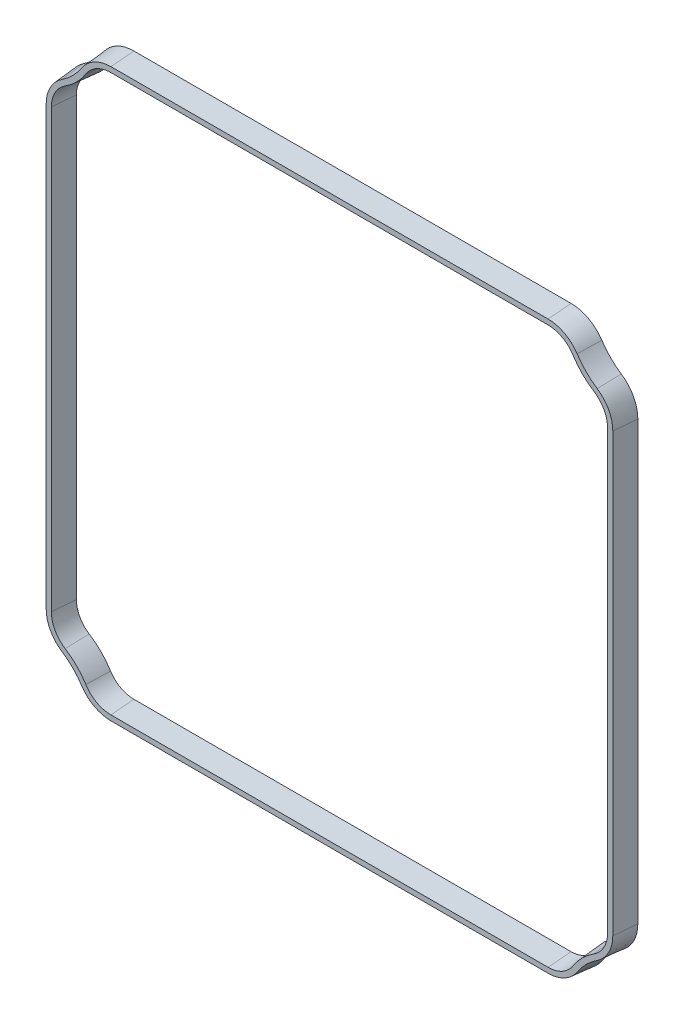
SolidWorks part; units mm, degrees
ref_plane "Front Plane" through (0, 0, 0) normal (0, 0, 1) x (1, 0, 0)
ref_plane "Top Plane" through (0, 0, 0) normal (0, 1, 0) x (1, 0, 0)
ref_plane "Right Plane" through (0, 0, 0) normal (1, 0, 0) x (0, 0, -1)
sketch "Sketch1" plane through (0, 0, 0) normal (0, 0, 1) x (1, 0, 0)
  line L4 (64.5, 11.25) -> (64.5, 58.75)
  line L5 (10.75, 5) -> (58.25, 5)
  line L6 (4.5, 58.75) -> (4.5, 11.25)
  line L7 (58.25, 65) -> (10.75, 65)
  line L8 (64.5, 11.25) -> (64.5, 58.75)
  line L9 (10.75, 5) -> (58.25, 5)
  line L10 (4.5, 58.75) -> (4.5, 11.25)
  line L11 (58.25, 65) -> (10.75, 65)
  line L12 (65.5, 11.25) -> (65.5, 58.75)
  line L13 (58.25, 66) -> (10.75, 66)
  line L14 (3.5, 58.75) -> (3.5, 11.25)
  line L15 (10.75, 4) -> (58.25, 4)
  line L16 (65.5, 11.25) -> (65.5, 58.75)
  line L17 (58.25, 66) -> (10.75, 66)
  line L18 (3.5, 58.75) -> (3.5, 11.25)
  line L19 (10.75, 4) -> (58.25, 4)
  arc A12 (60.7842, 63.6056) -> (58.25, 65) centre (58.25, 62) ccw
  arc A13 (60.7842, 63.6056) -> (63.1056, 61.2842) centre (67.1196, 67.6196) ccw
  arc A14 (64.5, 58.75) -> (63.1056, 61.2842) centre (61.5, 58.75) ccw
  arc A15 (63.1056, 8.7158) -> (64.5, 11.25) centre (61.5, 11.25) ccw
  arc A16 (63.1056, 8.7158) -> (60.7842, 6.3944) centre (67.1196, 2.3804) ccw
  arc A17 (58.25, 5) -> (60.7842, 6.3944) centre (58.25, 8) ccw
  arc A18 (8.2158, 6.3944) -> (10.75, 5) centre (10.75, 8) ccw
  arc A19 (8.2158, 6.3944) -> (5.8944, 8.7158) centre (1.8804, 2.3804) ccw
  arc A20 (4.5, 11.25) -> (5.8944, 8.7158) centre (7.5, 11.25) ccw
  arc A21 (5.8944, 61.2842) -> (4.5, 58.75) centre (7.5, 58.75) ccw
  arc A22 (5.8944, 61.2842) -> (8.2158, 63.6056) centre (1.8804, 67.6196) ccw
  arc A23 (10.75, 65) -> (8.2158, 63.6056) centre (10.75, 62) ccw
  arc A24 (60.7842, 63.6056) -> (58.25, 65) centre (58.25, 62) ccw
  arc A25 (60.7842, 63.6056) -> (63.1056, 61.2842) centre (67.1196, 67.6196) ccw
  arc A26 (64.5, 58.75) -> (63.1056, 61.2842) centre (61.5, 58.75) ccw
  arc A27 (63.1056, 8.7158) -> (64.5, 11.25) centre (61.5, 11.25) ccw
  arc A28 (63.1056, 8.7158) -> (60.7842, 6.3944) centre (67.1196, 2.3804) ccw
  arc A29 (58.25, 5) -> (60.7842, 6.3944) centre (58.25, 8) ccw
  arc A30 (8.2158, 6.3944) -> (10.75, 5) centre (10.75, 8) ccw
  arc A31 (8.2158, 6.3944) -> (5.8944, 8.7158) centre (1.8804, 2.3804) ccw
  arc A32 (4.5, 11.25) -> (5.8944, 8.7158) centre (7.5, 11.25) ccw
  arc A33 (5.8944, 61.2842) -> (4.5, 58.75) centre (7.5, 58.75) ccw
  arc A34 (5.8944, 61.2842) -> (8.2158, 63.6056) centre (1.8804, 67.6196) ccw
  arc A35 (10.75, 65) -> (8.2158, 63.6056) centre (10.75, 62) ccw
  arc A36 (58.25, 4) -> (61.5866, 5.7938) centre (58.25, 8) ccw
  arc A37 (63.7062, 7.9134) -> (61.5866, 5.7938) centre (67.8427, 1.6573) ccw
  arc A38 (63.7062, 7.9134) -> (65.5, 11.25) centre (61.5, 11.25) ccw
  arc A39 (65.5, 58.75) -> (63.7062, 62.0866) centre (61.5, 58.75) ccw
  arc A40 (61.5866, 64.2062) -> (63.7062, 62.0866) centre (67.8427, 68.3427) ccw
  arc A41 (61.5866, 64.2062) -> (58.25, 66) centre (58.25, 62) ccw
  arc A42 (10.75, 66) -> (7.4134, 64.2062) centre (10.75, 62) ccw
  arc A43 (5.2938, 62.0866) -> (7.4134, 64.2062) centre (1.1573, 68.3427) ccw
  arc A44 (5.2938, 62.0866) -> (3.5, 58.75) centre (7.5, 58.75) ccw
  arc A45 (3.5, 11.25) -> (5.2938, 7.9134) centre (7.5, 11.25) ccw
  arc A46 (7.4134, 5.7938) -> (5.2938, 7.9134) centre (1.1573, 1.6573) ccw
  arc A47 (7.4134, 5.7938) -> (10.75, 4) centre (10.75, 8) ccw
  arc A48 (58.25, 4) -> (61.5866, 5.7938) centre (58.25, 8) ccw
  arc A49 (63.7062, 7.9134) -> (61.5866, 5.7938) centre (67.8427, 1.6573) ccw
  arc A50 (63.7062, 7.9134) -> (65.5, 11.25) centre (61.5, 11.25) ccw
  arc A51 (65.5, 58.75) -> (63.7062, 62.0866) centre (61.5, 58.75) ccw
  arc A52 (61.5866, 64.2062) -> (63.7062, 62.0866) centre (67.8427, 68.3427) ccw
  arc A53 (61.5866, 64.2062) -> (58.25, 66) centre (58.25, 62) ccw
  arc A54 (10.75, 66) -> (7.4134, 64.2062) centre (10.75, 62) ccw
  arc A55 (5.2938, 62.0866) -> (7.4134, 64.2062) centre (1.1573, 68.3427) ccw
  arc A56 (5.2938, 62.0866) -> (3.5, 58.75) centre (7.5, 58.75) ccw
  arc A57 (3.5, 11.25) -> (5.2938, 7.9134) centre (7.5, 11.25) ccw
  arc A58 (7.4134, 5.7938) -> (5.2938, 7.9134) centre (1.1573, 1.6573) ccw
  arc A59 (7.4134, 5.7938) -> (10.75, 4) centre (10.75, 8) ccw
  dimension "D1" = 0
  dimension "D2" = 0
extrude "Boss-Extrude1" add sketch "Sketch1" along normal blind 2.5 draft 5
